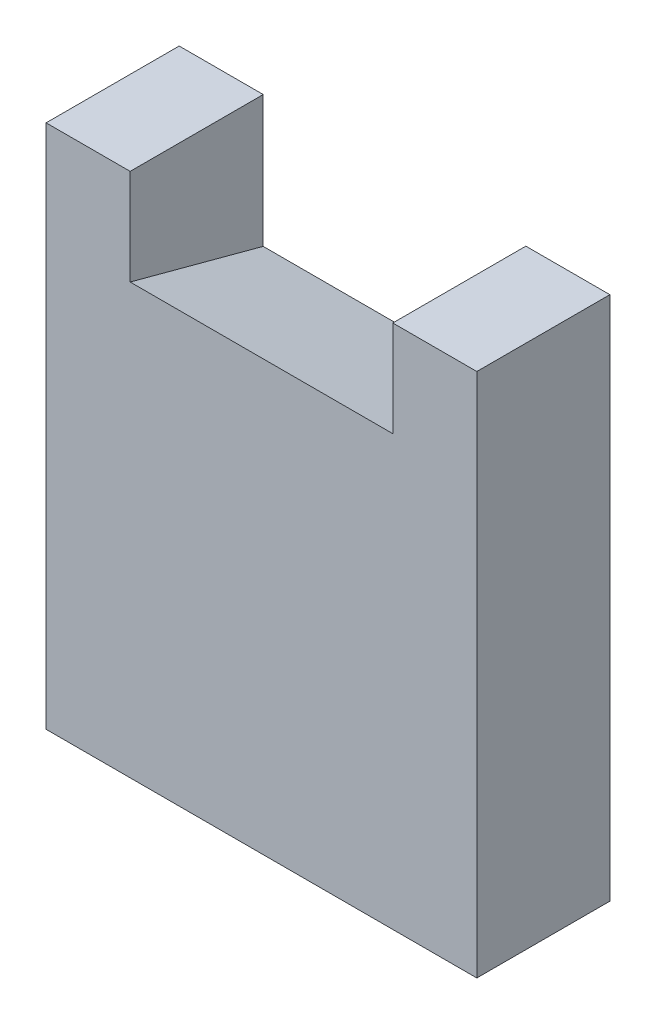
SolidWorks part; units mm, degrees
ref_plane "前视基准面" through (0, 0, 0) normal (0, 0, 1) x (1, 0, 0)
ref_plane "上视基准面" through (0, 0, 0) normal (0, 1, 0) x (1, 0, 0)
ref_plane "右视基准面" through (0, 0, 0) normal (1, 0, 0) x (0, 0, -1)
sketch "草图1" plane through (0, 0, 0) normal (0, 0, 1) x (1, 0, 0)
  line L1 (0, 0) -> (24.6, 0)
  line L2 (0, 0) -> (0, -30)
  line L3 (0, -30) -> (24.6, -30)
  line L4 (24.6, 0) -> (24.6, -30)
  line L5 (4.8, 0) -> (19.8, 0)
  line L6 (4.8, 0) -> (4.8, -5.475)
  line L7 (4.8, -5.475) -> (19.8, -5.475)
  line L8 (19.8, 0) -> (19.8, -5.475)
  point P9 (12.3, 0)
  dimension "D1" = 30
  dimension "D2" = 24.6
  dimension "D3" = 15
  dimension "D4" = 24.525
extrude "凸台-拉伸1" add sketch "草图1" along normal blind 7.6 contours L1 L8 L7 L6 L2 L3 L4
draft "拔模5" type of draft neutral plane draft angle 15 faces to draft 1 face at (12.3, -5.475, 3.8) neutral plane through (0, 0, 7.6) neutral plane normal (0, 0, 1) reverse direction yes parameters "D1"=15
